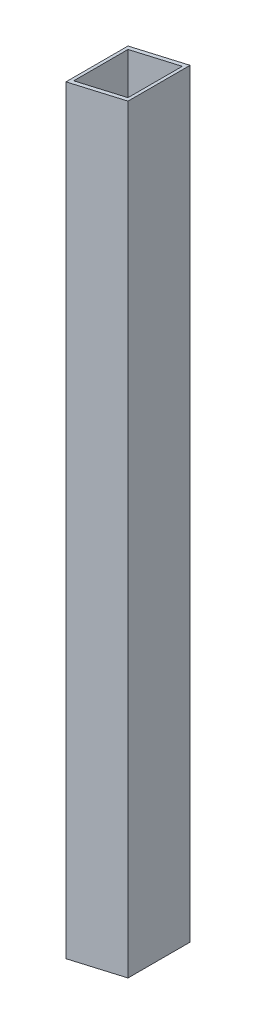
SolidWorks part; units mm, degrees
ref_plane "Alzado" through (0, 0, 0) normal (0, 0, 1) x (1, 0, 0)
ref_plane "Planta" through (0, 0, 0) normal (0, 1, 0) x (1, 0, 0)
ref_plane "Vista lateral" through (0, 0, 0) normal (1, 0, 0) x (0, 0, -1)
sketch "Croquis1" plane through (0, 0, 0) normal (0, 1, 0) x (1, 0, 0)
  line L0 (4.7625, -4.7625) -> (71.4375, -4.7625)
  line L1 (0, 0) -> (76.2, 0)
  line L2 (0, 0) -> (0, -76.2)
  line L3 (0, -76.2) -> (76.2, -76.2)
  line L4 (76.2, 0) -> (76.2, -76.2)
  line L5 (71.4375, -4.7625) -> (71.4375, -71.4375)
  line L6 (4.7625, -71.4375) -> (71.4375, -71.4375)
  line L7 (4.7625, -4.7625) -> (4.7625, -71.4375)
  dimension "D1" = 76.2
  dimension "D2" = 76.2
  dimension "D3" = 4.7625
extrude "Saliente-Extruir1" add sketch "Croquis1" along normal blind 950
sketch "Croquis2" plane through (0, 0, 76.2) normal (0, 0, 1) x (1, 0, 0)
  line L0 (0, 0) -> (76.2, 17.5922)
  line L1 (76.2, 950) -> (76.2, 0) construction
  line L2 (0, 0) -> (76.2, 0) construction
  line L3 (76.2, 17.5922) -> (76.2, 0)
  line L4 (76.2, 0) -> (0, 0)
  dimension "D1" = 13
extrude "Cortar-Extruir1" cut sketch "Croquis2" against normal up to surface (76.2 mm away) up to face at (38.1, 475, 0)
sketch "Croquis3" plane through (0, 0, 76.2) normal (0, 0, 1) x (1, 0, 0)
  line L0 (76.2, 950) -> (0, 932.4078)
  line L1 (0, 950) -> (0, 0) construction
  line L2 (0, 950) -> (76.2, 950) construction
  line L3 (76.2, 950) -> (0, 950)
  line L4 (0, 950) -> (0, 932.4078)
  dimension "D1" = 13
extrude "Cortar-Extruir2" cut sketch "Croquis3" against normal blind 76.2
